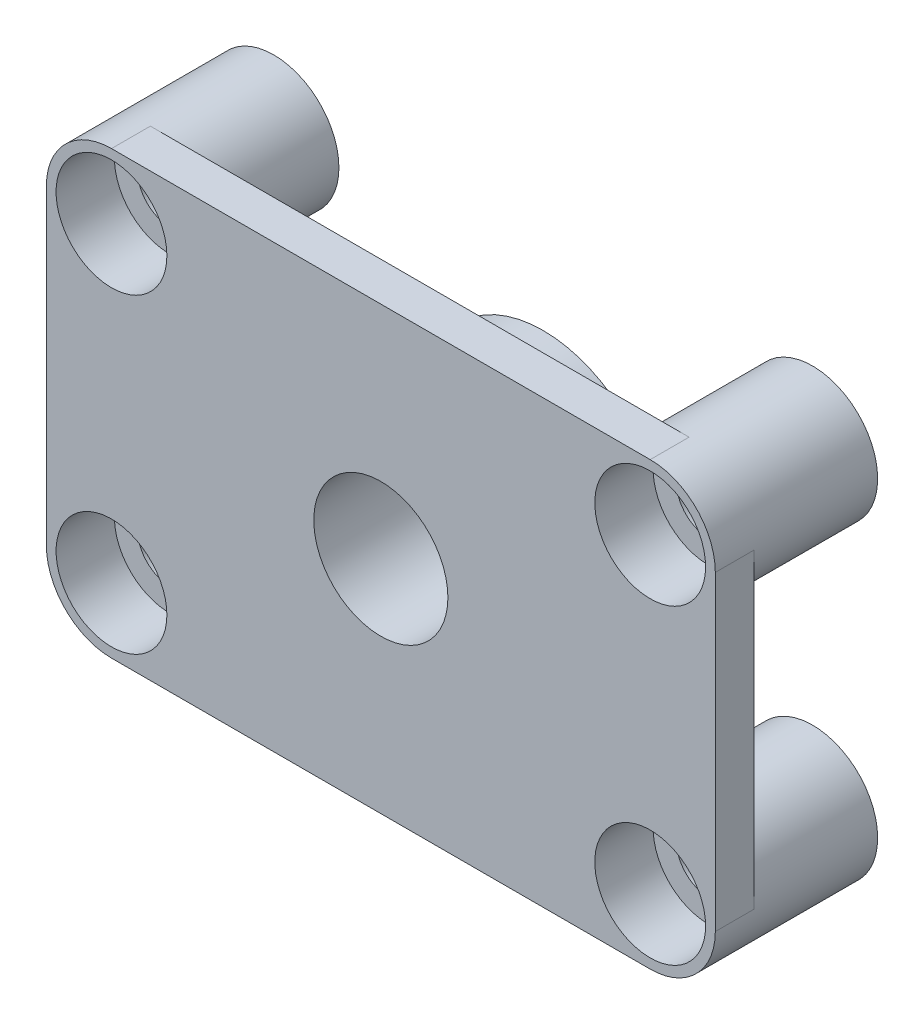
SolidWorks part; units mm, degrees
ref_plane "Front Plane" through (0, 0, 0) normal (0, 0, 1) x (1, 0, 0)
ref_plane "Top Plane" through (0, 0, 0) normal (0, 1, 0) x (1, 0, 0)
ref_plane "Right Plane" through (0, 0, 0) normal (1, 0, 0) x (0, 0, -1)
sketch "Sketch1" plane through (0, 0, 0) normal (0, 0, 1) x (1, 0, 0)
  line L0 (0, 0) -> (0, 13.2477) construction
  line L1 (-13.8564, 8) -> (0, 0) construction
  line L2 (0, 0) -> (-18.9296, 0) construction
  circle A1 centre (-13.8564, 8) radius 1.65
  circle A2 centre (-13.8564, -8) radius 1.65
  circle A3 centre (13.8564, -8) radius 1.65
  circle A4 centre (13.8564, 8) radius 1.65
  circle A5 centre (-13.8564, 8) radius 3.35
  circle A6 centre (-13.8564, -8) radius 3.35
  circle A7 centre (13.8564, -8) radius 3.35
  circle A8 centre (13.8564, 8) radius 3.35
  circle A9 centre (0, 0) radius 6
  circle A10 centre (0, 0) radius 3.45
  dimension "D1" = 16
  dimension "D3" = 3.3
  dimension "D5" = 12
  dimension "D6" = 6.9
  dimension "D2" = 60
  dimension "D4" = 1.7
extrude "Boss-Extrude1" add sketch "Sketch1" along normal blind 6.35
sketch "Sketch2" plane through (0, 0, 6.35) normal (0, 0, 1) x (1, 0, 0)
  line L0 (-17.2064, 8) -> (-17.2064, -8)
  line L1 (-13.8564, 11.35) -> (13.8564, 11.35)
  line L2 (17.2064, -8) -> (17.2064, 8)
  line L3 (13.8564, -11.35) -> (-13.8564, -11.35)
  circle A0 centre (13.8564, 8) radius 3.35 construction
  circle A1 centre (13.8564, -8) radius 3.35 construction
  circle A2 centre (-13.8564, -8) radius 3.35 construction
  circle A3 centre (0, 0) radius 6 construction
  circle A4 centre (-13.8564, 8) radius 3.35 construction
  arc A5 (17.2064, 8) -> (13.8564, 11.35) centre (13.8564, 8) ccw
  arc A6 (13.8564, -11.35) -> (17.2064, -8) centre (13.8564, -8) ccw
  arc A7 (-17.2064, -8) -> (-13.8564, -11.35) centre (-13.8564, -8) ccw
  circle A8 centre (0, 0) radius 6
  arc A9 (-13.8564, 11.35) -> (-17.2064, 8) centre (-13.8564, 8) ccw
  circle A10 centre (13.8564, -8) radius 1.65 construction
  circle A11 centre (13.8564, 8) radius 1.65 construction
  circle A12 centre (0, 0) radius 3.45 construction
  circle A13 centre (-13.8564, -8) radius 1.65 construction
  circle A14 centre (-13.8564, 8) radius 1.65 construction
  circle A15 centre (13.8564, -8) radius 1.65
  circle A16 centre (13.8564, 8) radius 1.65
  circle A17 centre (0, 0) radius 3.45
  circle A18 centre (-13.8564, -8) radius 1.65
  circle A19 centre (-13.8564, 8) radius 1.65
  circle M10 centre (0, 0) radius 6
  circle M11 centre (0, 0) radius 3.45
extrude "Boss-Extrude2" add sketch "Sketch2" along normal blind 2 contours L1 A9 L0 A7 L3 A6 L2 A5 A19 A18 A16 A15 M10 | M10 M11
sketch "Sketch3" plane through (0, 0, 8.35) normal (0, 0, 1) x (1, 0, 0)
  circle A0 centre (-13.8564, 8) radius 2.85
  circle A1 centre (-13.8564, -8) radius 2.85
  circle A2 centre (13.8564, -8) radius 2.85
  circle A3 centre (13.8564, 8) radius 2.85
  dimension "D1" = 5.7
extrude "Cut-Extrude1" cut sketch "Sketch3" against normal blind 3
